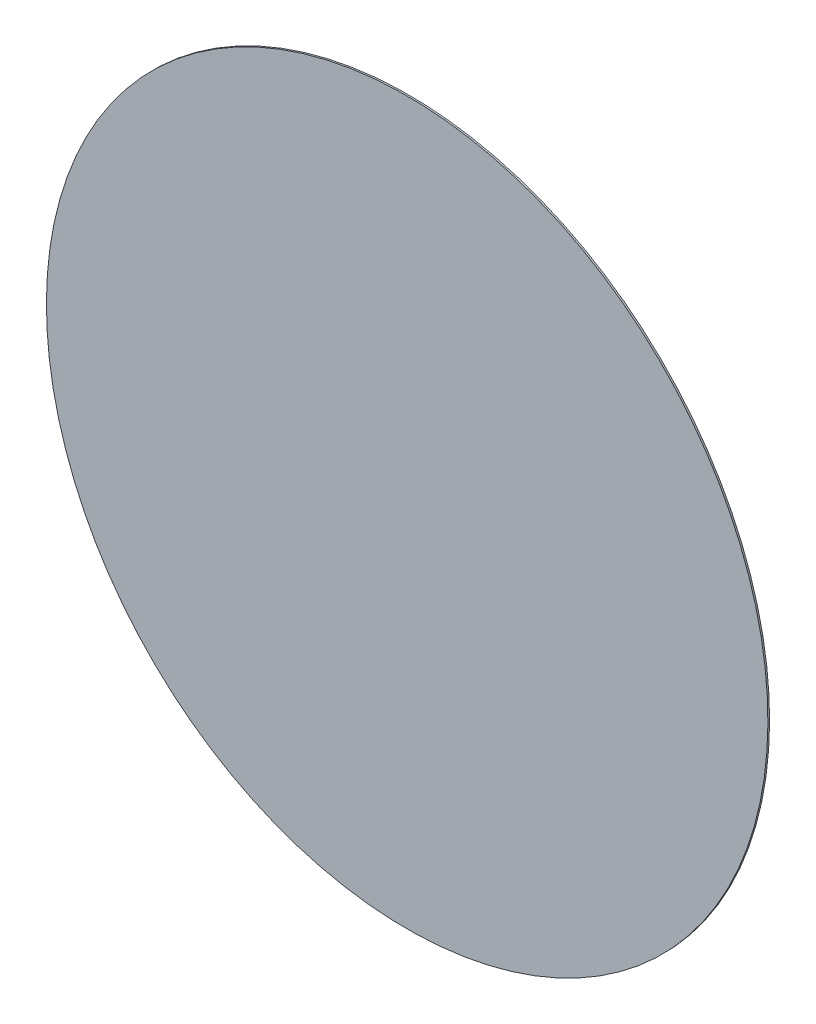
SolidWorks part; units mm, degrees
ref_plane "Front Plane" through (0, 0, 0) normal (0, 0, 1) x (1, 0, 0)
ref_plane "Top Plane" through (0, 0, 0) normal (0, 1, 0) x (1, 0, 0)
ref_plane "Right Plane" through (0, 0, 0) normal (1, 0, 0) x (0, 0, -1)
sketch "CurveSketch" plane through (0, 0, 0) normal (0, 0, 1) x (1, 0, 0)
  line L0 (53.6981, -16.5987) -> (53.6856, -16.535)
  arc A0 (53.6856, -16.535) -> (53.6981, -16.5987) centre (17.193, -23.719) ccw
  dimension "D1" = 37.193
extrude "CurveBoss" add sketch "CurveSketch" along normal blind 0.173
